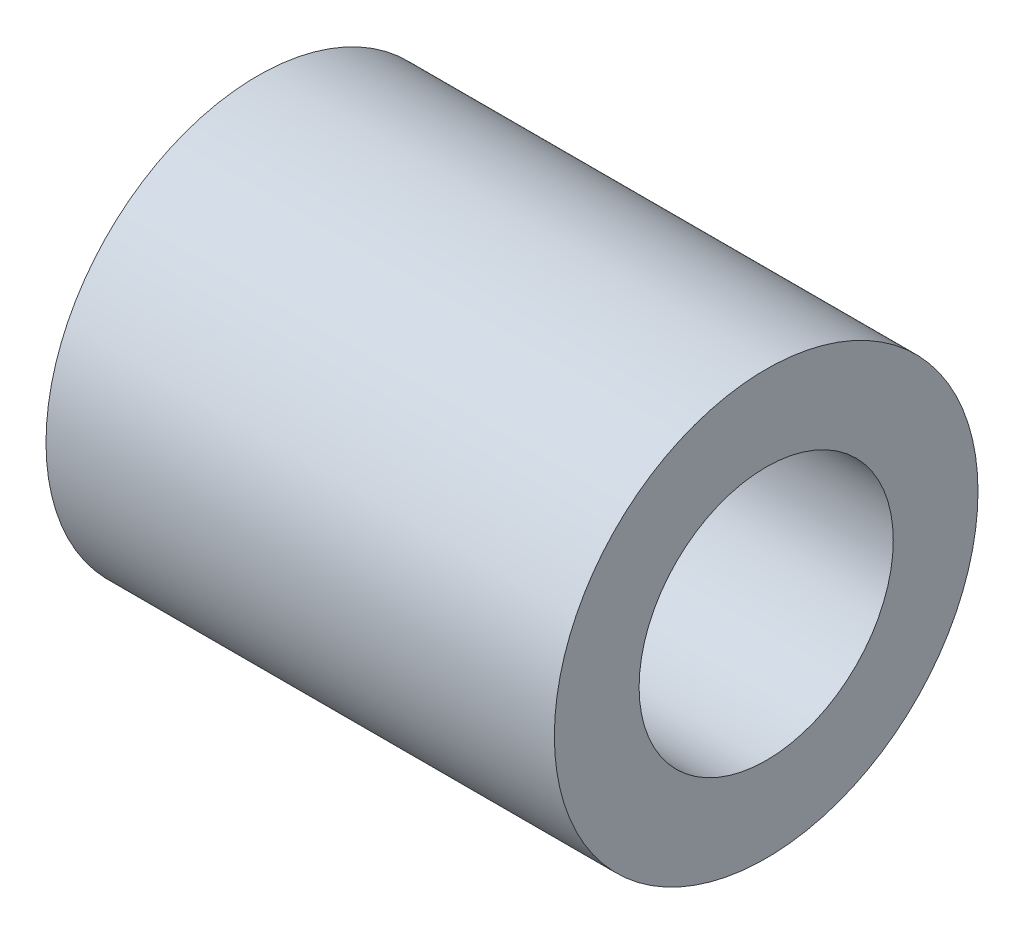
SolidWorks part; units mm, degrees
ref_plane "Front Plane" through (0, 0, 0) normal (0, 0, 1) x (1, 0, 0)
ref_plane "Top Plane" through (0, 0, 0) normal (0, 1, 0) x (1, 0, 0)
ref_plane "Right Plane" through (0, 0, 0) normal (1, 0, 0) x (0, 0, -1)
sketch "Sketch1" plane through (0, 0, 0) normal (0, 0, 1) x (1, 0, 0)
  line L1 (0, 5) -> (12, 5)
  line L2 (12, 5) -> (12, 3)
  line L3 (12, 3) -> (0, 3)
  line L6 (0, 5) -> (0, 3)
  line L7 (0, 0) -> (11.6671, 0) construction
  dimension "D1" = 3
  dimension "D2" = 5
  dimension "D3" = 12
revolve "Revolve1" add sketch "Sketch1" angle 360 about L7
